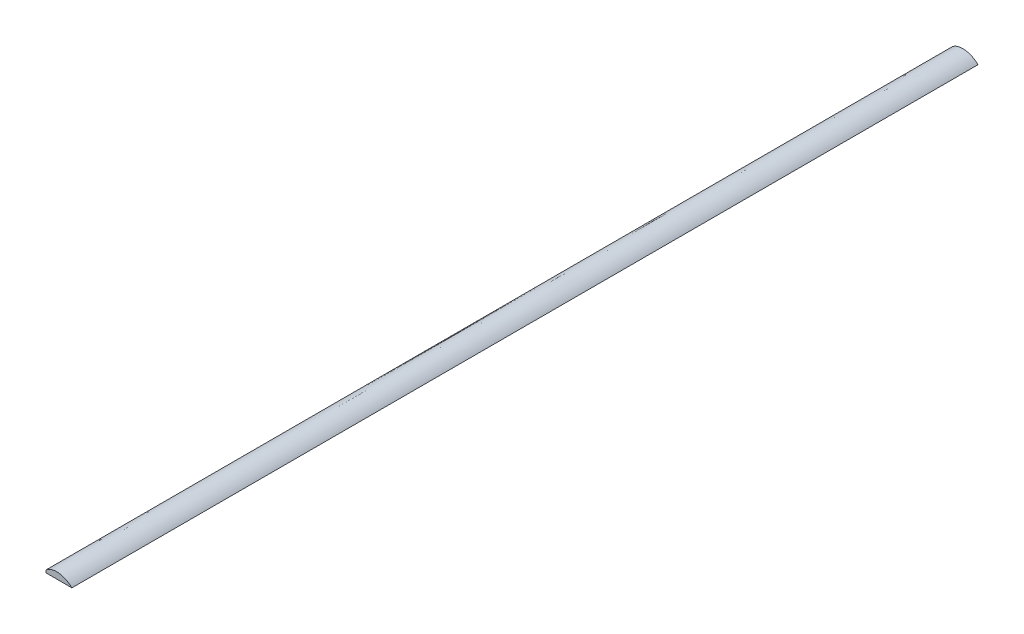
SolidWorks part; units mm, degrees
ref_plane "Front Plane" through (0, 0, 0) normal (0, 0, 1) x (1, 0, 0)
ref_plane "Top Plane" through (0, 0, 0) normal (0, 1, 0) x (1, 0, 0)
ref_plane "Right Plane" through (0, 0, 0) normal (1, 0, 0) x (0, 0, -1)
sketch "Sketch1" plane through (0, 0, 0) normal (0, 0, 1) x (1, 0, 0)
  line L0 (0, 0) -> (2, 0)
  line L1 (0, 0) -> (0, 0.2)
  spline S0 degree 3 poles (0, 0.2) (0.5607, 0.701) (1.5092, 0.5071) (2, 0) knots 0 0 0 0 1 1 1 1
  point P5 (1.152, 0.6385)
  point P7 (0.5549, 0.4688)
  point P8 (0.4075, 0.4307)
  point P9 (1.3343, 0.4072)
  dimension "D1" = 2
  dimension "D2" = 0.2
extrude "Boss-Extrude1" add sketch "Sketch1" against normal blind 70
